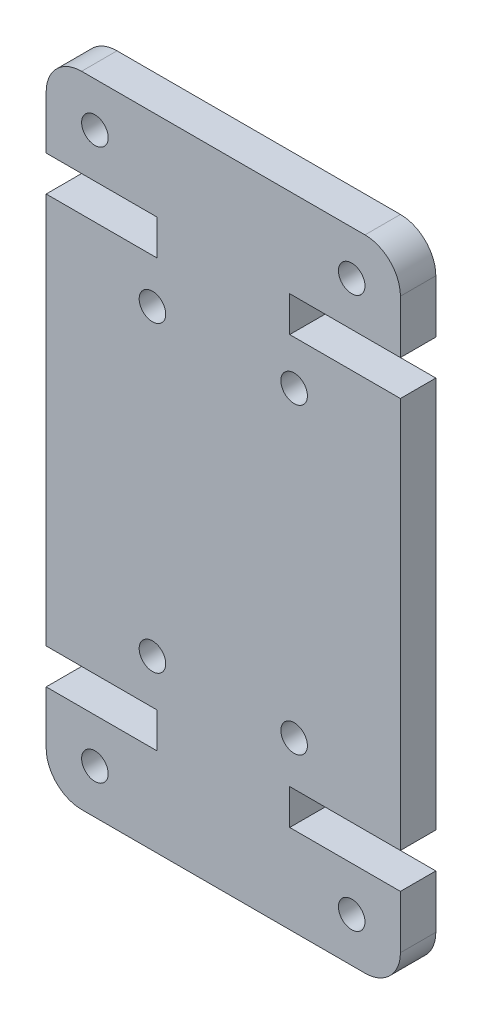
SolidWorks part; units mm, degrees
material "Acrylic (Medium-high impact)"
ref_plane "Front Plane" through (0, 0, 0) normal (0, 0, 1) x (1, 0, 0)
ref_plane "Top Plane" through (0, 0, 0) normal (0, 1, 0) x (1, 0, 0)
ref_plane "Right Plane" through (0, 0, 0) normal (1, 0, 0) x (0, 0, -1)
sketch "Model" plane through (0, 0, 0) normal (0, 0, 1) x (1, 0, 0)
  line L61 (1967.1098, 1230.3847) -> (1983.1098, 1230.3847)
  line L62 (1965.1098, 1228.3847) -> (1965.1098, 1225.3847)
  line L63 (1985.1098, 1225.3847) -> (1985.1098, 1228.3847)
  line L64 (1971.3598, 1225.3847) -> (1965.1098, 1225.3847)
  line L65 (1978.8598, 1225.3847) -> (1985.1098, 1225.3847)
  line L66 (1971.3598, 1223.3847) -> (1965.1098, 1223.3847)
  line L67 (1978.8598, 1223.3847) -> (1985.1098, 1223.3847)
  line L68 (1971.3598, 1225.3847) -> (1971.3598, 1223.3847)
  line L69 (1978.8598, 1225.3847) -> (1978.8598, 1223.3847)
  line L123 (1967.1098, 1194.2847) -> (1983.1098, 1194.2847)
  line L124 (1965.1098, 1196.2847) -> (1965.1098, 1199.2847)
  line L125 (1985.1098, 1199.2847) -> (1985.1098, 1196.2847)
  line L126 (1971.3598, 1199.2847) -> (1965.1098, 1199.2847)
  line L127 (1978.8598, 1199.2847) -> (1985.1098, 1199.2847)
  line L128 (1971.3598, 1201.2847) -> (1965.1098, 1201.2847)
  line L129 (1978.8598, 1201.2847) -> (1985.1098, 1201.2847)
  line L130 (1971.3598, 1199.2847) -> (1971.3598, 1201.2847)
  line L131 (1978.8598, 1199.2847) -> (1978.8598, 1201.2847)
  line L132 (1965.1098, 1223.3847) -> (1965.1098, 1201.2847)
  line L133 (1985.1098, 1223.3847) -> (1985.1098, 1201.2847)
  arc A23 (1985.1098, 1228.3847) -> (1983.1098, 1230.3847) centre (1983.1098, 1228.3847) ccw
  arc A24 (1967.1098, 1230.3847) -> (1965.1098, 1228.3847) centre (1967.1098, 1228.3847) ccw
  circle A27 centre (1979.1098, 1220.8847) radius 0.75
  circle A28 centre (1971.1098, 1220.8847) radius 0.75
  arc A45 (1983.1098, 1194.2847) -> (1985.1098, 1196.2847) centre (1983.1098, 1196.2847) ccw
  arc A46 (1965.1098, 1196.2847) -> (1967.1098, 1194.2847) centre (1967.1098, 1196.2847) ccw
  circle A47 centre (1979.1098, 1203.7847) radius 0.75
  circle A48 centre (1971.1098, 1203.7847) radius 0.75
  circle A49 centre (1982.3598, 1196.7847) radius 0.75
  circle A50 centre (1967.8598, 1196.7847) radius 0.75
  circle A100 centre (1982.3598, 1227.8847) radius 0.75
  circle A101 centre (1967.8598, 1227.8847) radius 0.75
extrude "Boss-Extrude1" add sketch "Model" along normal blind 2
